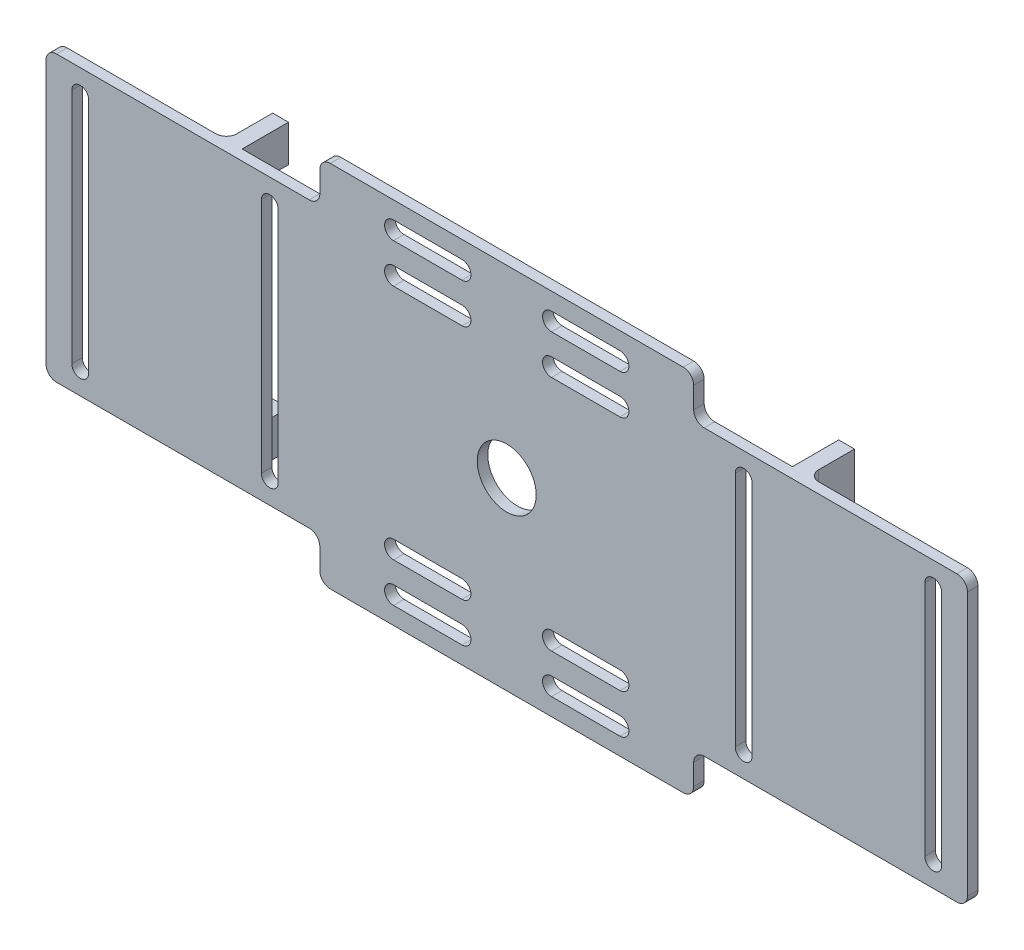
SolidWorks part; units mm, degrees
ref_plane "前基準面" through (0, 0, 0) normal (0, 0, 1) x (1, 0, 0)
ref_plane "上基準面" through (0, 0, 0) normal (0, 1, 0) x (1, 0, 0)
ref_plane "右基準面" through (0, 0, 0) normal (1, 0, 0) x (0, 0, -1)
sketch "草圖1" plane through (0, 0, 0) normal (0, 0, 1) x (1, 0, 0)
  line L0 (35.5, 33) -> (35.5, 29)
  line L1 (-33.5, 35) -> (33.5, 35)
  line L2 (-87.5, 25) -> (-87.5, -25)
  line L3 (-33.5, -35) -> (33.5, -35)
  line L4 (87.5, 25) -> (87.5, -25)
  line L5 (-85, 35) -> (85, -35) construction
  line L6 (-85, -35) -> (85, 35) construction
  line L7 (37.5, 27) -> (85.5, 27)
  line L8 (0, 72.342) -> (0, -45.5052) construction
  line L9 (-37.5, 27) -> (-85.5, 27)
  line L10 (124.9211, 0) -> (-91.026, 0) construction
  line L11 (-35.5, 33) -> (-35.5, 29)
  line L12 (37.5, -27) -> (85.5, -27)
  line L13 (35.5, -33) -> (35.5, -29)
  line L14 (-35.5, -33) -> (-35.5, -29)
  line L15 (-37.5, -27) -> (-85.5, -27)
  arc A0 (35.5, 33) -> (33.5, 35) centre (33.5, 33) ccw
  arc A1 (37.5, 27) -> (35.5, 29) centre (37.5, 29) cw
  arc A2 (87.5, 25) -> (85.5, 27) centre (85.5, 25) ccw
  arc A3 (-87.5, 25) -> (-85.5, 27) centre (-85.5, 25) cw
  arc A4 (-37.5, 27) -> (-35.5, 29) centre (-37.5, 29) ccw
  arc A5 (-35.5, 33) -> (-33.5, 35) centre (-33.5, 33) cw
  arc A6 (87.5, -25) -> (85.5, -27) centre (85.5, -25) cw
  arc A7 (37.5, -27) -> (35.5, -29) centre (37.5, -29) ccw
  arc A8 (35.5, -33) -> (33.5, -35) centre (33.5, -33) cw
  arc A9 (-35.5, -33) -> (-33.5, -35) centre (-33.5, -33) ccw
  arc A10 (-37.5, -27) -> (-35.5, -29) centre (-37.5, -29) cw
  arc A11 (-87.5, -25) -> (-85.5, -27) centre (-85.5, -25) ccw
  point P0 (0, 0)
  point P13 (35.5, 27)
  point P29 (-35.5, 27)
  point P39 (35.5, -27)
  point P49 (-35.5, -27)
  dimension "D1" = 2
  dimension "D2" = 2
  dimension "D3" = 2
  dimension "D4" = 175
  dimension "D5" = 70
  dimension "D6" = 52
  dimension "D7" = 8
extrude "填料-伸長1" add sketch "草圖1" along normal blind 2
sketch "草圖2" plane through (0, 0, 2) normal (0, 0, 1) x (1, 0, 0)
  line L0 (-1000, 0) -> (49000, 0) construction
  line L1 (45, -986.1952) -> (45, 49013.8048) construction
  line L2 (-81, -962.7943) -> (-81, 49037.2057) construction
  line L3 (45, -22.5) -> (45, 22.5) construction
  line L4 (43.4, -22.5) -> (43.4, 22.5)
  line L5 (46.6, -22.5) -> (46.6, 22.5)
  line L6 (-45, -1000) -> (-45, 49000) construction
  line L7 (-45, -22.5) -> (-45, 22.5) construction
  line L8 (-46.6, -22.5) -> (-46.6, 22.5)
  line L9 (-43.4, -22.5) -> (-43.4, 22.5)
  line L10 (0, -1000) -> (0, 49000) construction
  line L11 (-1005.6924, 30) -> (48994.3076, 30) construction
  line L12 (-1002.3566, -30) -> (48997.6434, -30) construction
  line L13 (21.5, 30) -> (8.5, 30) construction
  line L16 (21.5, 28.3) -> (8.5, 28.3)
  line L19 (81, -968.4295) -> (81, 49031.5705) construction
  line L20 (-81, -22.5) -> (-81, 22.5) construction
  line L21 (-82.6, -22.5) -> (-82.6, 22.5)
  line L22 (-79.4, -22.5) -> (-79.4, 22.5)
  line L23 (81, -22.5) -> (81, 22.5) construction
  line L24 (79.4, -22.5) -> (79.4, 22.5)
  line L25 (82.6, -22.5) -> (82.6, 22.5)
  line L26 (21.5, 31.7) -> (8.5, 31.7)
  line L27 (21.5, 22.5) -> (8.5, 22.5) construction
  line L28 (21.5, 20.8) -> (8.5, 20.8)
  line L29 (21.5, 24.2) -> (8.5, 24.2)
  line L30 (-21.5, 30) -> (-8.5, 30) construction
  line L31 (-21.5, 28.3) -> (-8.5, 28.3)
  line L32 (-21.5, 31.7) -> (-8.5, 31.7)
  line L33 (-21.5, 22.5) -> (-8.5, 22.5) construction
  line L34 (-21.5, 20.8) -> (-8.5, 20.8)
  line L35 (-21.5, 24.2) -> (-8.5, 24.2)
  line L36 (21.5, -30) -> (8.5, -30) construction
  line L37 (21.5, -28.3) -> (8.5, -28.3)
  line L38 (21.5, -31.7) -> (8.5, -31.7)
  line L39 (21.5, -22.5) -> (8.5, -22.5) construction
  line L40 (21.5, -20.8) -> (8.5, -20.8)
  line L41 (21.5, -24.2) -> (8.5, -24.2)
  line L42 (-21.5, -30) -> (-8.5, -30) construction
  line L43 (-21.5, -28.3) -> (-8.5, -28.3)
  line L44 (-21.5, -31.7) -> (-8.5, -31.7)
  line L45 (-21.5, -22.5) -> (-8.5, -22.5) construction
  line L46 (-21.5, -20.8) -> (-8.5, -20.8)
  line L47 (-21.5, -24.2) -> (-8.5, -24.2)
  arc A0 (43.4, -22.5) -> (46.6, -22.5) centre (45, -22.5) ccw
  arc A1 (46.6, 22.5) -> (43.4, 22.5) centre (45, 22.5) ccw
  arc A2 (-46.6, -22.5) -> (-43.4, -22.5) centre (-45, -22.5) ccw
  arc A3 (-43.4, 22.5) -> (-46.6, 22.5) centre (-45, 22.5) ccw
  arc A12 (-82.6, -22.5) -> (-79.4, -22.5) centre (-81, -22.5) ccw
  arc A13 (-79.4, 22.5) -> (-82.6, 22.5) centre (-81, 22.5) ccw
  arc A14 (79.4, -22.5) -> (82.6, -22.5) centre (81, -22.5) ccw
  arc A15 (82.6, 22.5) -> (79.4, 22.5) centre (81, 22.5) ccw
  circle A16 centre (0, 0) radius 5.6
  arc A17 (21.5, 28.3) -> (21.5, 31.7) centre (21.5, 30) ccw
  arc A18 (8.5, 31.7) -> (8.5, 28.3) centre (8.5, 30) ccw
  arc A19 (21.5, 20.8) -> (21.5, 24.2) centre (21.5, 22.5) ccw
  arc A20 (8.5, 24.2) -> (8.5, 20.8) centre (8.5, 22.5) ccw
  arc A21 (-21.5, 28.3) -> (-21.5, 31.7) centre (-21.5, 30) cw
  arc A22 (-8.5, 31.7) -> (-8.5, 28.3) centre (-8.5, 30) cw
  arc A23 (-21.5, 20.8) -> (-21.5, 24.2) centre (-21.5, 22.5) cw
  arc A24 (-8.5, 24.2) -> (-8.5, 20.8) centre (-8.5, 22.5) cw
  arc A25 (21.5, -28.3) -> (21.5, -31.7) centre (21.5, -30) cw
  arc A26 (8.5, -31.7) -> (8.5, -28.3) centre (8.5, -30) cw
  arc A27 (21.5, -20.8) -> (21.5, -24.2) centre (21.5, -22.5) cw
  arc A28 (8.5, -24.2) -> (8.5, -20.8) centre (8.5, -22.5) cw
  arc A29 (-21.5, -28.3) -> (-21.5, -31.7) centre (-21.5, -30) ccw
  arc A30 (-8.5, -31.7) -> (-8.5, -28.3) centre (-8.5, -30) ccw
  arc A31 (-21.5, -20.8) -> (-21.5, -24.2) centre (-21.5, -22.5) ccw
  arc A32 (-8.5, -24.2) -> (-8.5, -20.8) centre (-8.5, -22.5) ccw
  point P9 (45, 0)
  point P16 (-45, 0)
  point P31 (15, 30)
  point P39 (15, 22.5)
  point P47 (-81, 0)
  point P54 (81, 0)
  point P63 (-15, 30)
  point P70 (-15, 22.5)
  point P77 (15, -30)
  point P84 (15, -22.5)
  point P91 (-15, -30)
  point P98 (-15, -22.5)
  dimension "D10" = 1.7
  dimension "D20" = 11.2
  dimension "D12" = 8.5
  dimension "D2" = 45
  dimension "D3" = 3.2
  dimension "D4" = 90
  dimension "D5" = 45
  dimension "D6" = 3.2
  dimension "D7" = 45
  dimension "D8" = 60
  dimension "D9" = 30
  dimension "D11" = 13
  dimension "D13" = 2
  dimension "D14" = 162
  dimension "D15" = 81
  dimension "D16" = 3.2
  dimension "D17" = 45
  dimension "D18" = 45
  dimension "D19" = 3.2
extrude "除料-伸長1" cut sketch "草圖2" against normal through all
sketch "草圖5" plane through (0, 0, 2) normal (0, 0, 1) x (1, 0, 0)
  line L1 (-55.25, 27) -> (-52.25, 27)
  line L2 (-55.25, 27) -> (-55.25, -27)
  line L3 (-55.25, -27) -> (-52.25, -27)
  line L4 (-52.25, 27) -> (-52.25, -27)
  line L6 (0, 48.2539) -> (0, -45.9001) construction
  line L7 (52.25, 27) -> (52.25, -27)
  line L8 (55.25, -27) -> (52.25, -27)
  line L9 (55.25, 27) -> (55.25, -27)
  line L10 (55.25, 27) -> (52.25, 27)
  line L11 (-37.5, 27) -> (-85.5, 27) construction
  line L13 (-85.5, -27) -> (-37.5, -27) construction
  dimension "D1" = 3
  dimension "D2" = 52.25
extrude "填料-伸長2" add sketch "草圖5" against normal blind 10.8 contours L2 L3 L4 L1 | L7 L8 L9 L10
fillet "圓角1" radius 2 1 edges at (55.25, 0, 0)
sketch "草圖6" plane through (0, 0, -8.8) normal (0, 0, -1) x (-1, 0, 0)
  line L0 (-19.1896, 0) -> (94.9262, 0) construction
  line L1 (55.25, 27) -> (55.25, -27) construction
  line L2 (52.25, -20) -> (55.25, -20)
  line L3 (52.25, -20) -> (52.25, 20)
  line L4 (52.25, 20) -> (55.25, 20)
  line L5 (55.25, -20) -> (55.25, 20)
  line L6 (52.25, -20) -> (55.25, 20) construction
  line L7 (52.25, 20) -> (55.25, -20) construction
  line L8 (52.25, 27) -> (52.25, -27) construction
  point P2 (53.75, 0)
  dimension "D1" = 40
extrude "除料-伸長3" cut sketch "草圖6" against normal blind 6
fillet "圓角2" radius 2 2 edges at (-53.75, -20, -2.8) (-53.75, 20, -2.8)
fillet "圓角3" radius 2 1 edges at (-55.25, 0, 0)
